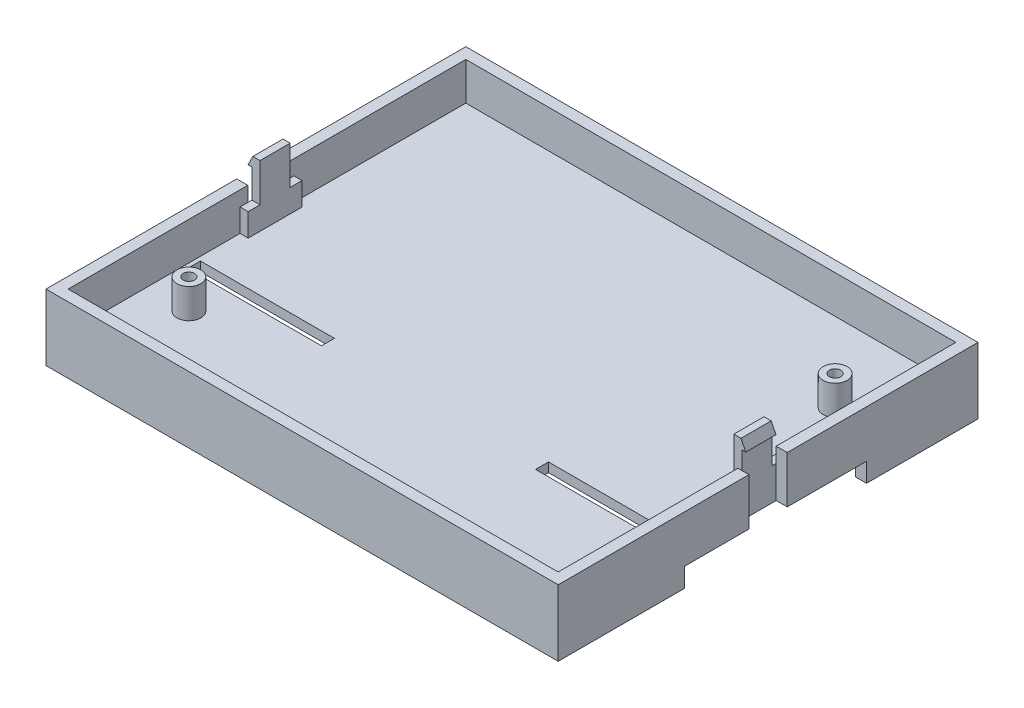
SolidWorks part; units mm, degrees
ref_plane "Alzado" through (0, 0, 0) normal (0, 0, 1) x (1, 0, 0)
ref_plane "Planta" through (0, 0, 0) normal (0, 1, 0) x (1, 0, 0)
ref_plane "Vista lateral" through (0, 0, 0) normal (1, 0, 0) x (0, 0, -1)
sketch "Sketch1" plane through (0, 0, 0) normal (0, 1, 0) x (1, 0, 0)
  line L1 (-53.5, -43.85) -> (53.5, -43.85)
  line L2 (-53.5, -43.85) -> (-53.5, 43.85)
  line L3 (-53.5, 43.85) -> (53.5, 43.85)
  line L4 (53.5, -43.85) -> (53.5, 43.85)
  line L5 (-53.5, -43.85) -> (53.5, 43.85) construction
  line L6 (-53.5, 43.85) -> (53.5, -43.85) construction
  point P0 (0, 0)
  dimension "D1" = 107
  dimension "D2" = 87.7
extrude "Boss-Extrude1" add sketch "Sketch1" along normal blind 13.85
sketch "Sketch2" plane through (0, 13.85, 0) normal (0, 1, 0) x (1, 0, 0)
  line L8 (51.19, -41.54) -> (51.19, 41.54)
  line L9 (51.19, 41.54) -> (-51.19, 41.54)
  line L10 (-51.19, 41.54) -> (-51.19, -41.54)
  line L11 (-51.19, -41.54) -> (51.19, -41.54)
  line L12 (51.19, -41.54) -> (51.19, 41.54)
  line L13 (51.19, 41.54) -> (-51.19, 41.54)
  line L14 (-51.19, 41.54) -> (-51.19, -41.54)
  line L15 (-51.19, -41.54) -> (51.19, -41.54)
  dimension "D1" = 2.31
extrude "Cut-Extrude1" cut sketch "Sketch2" against normal blind 7.9
sketch "Sketch3" plane through (0, 0, 0) normal (0, -1, 0) x (1, 0, 0)
  line L0 (-51.19, -41.54) -> (-51.19, 41.54) construction
  line L1 (-51.19, 41.54) -> (51.19, 41.54)
  line L2 (-51.19, 41.54) -> (-51.19, 19.24)
  line L3 (-51.19, 19.24) -> (-23.5, 19.24)
  line L4 (51.19, 41.54) -> (51.19, 19.24)
  line L5 (-51.19, 41.54) -> (51.19, 41.54) construction
  line L6 (51.19, 41.54) -> (51.19, -41.54) construction
  line L7 (-23.5, 19.24) -> (-23.5, 14.74)
  line L8 (-23.5, 14.74) -> (-49.4, 14.74)
  line L9 (-53.5, -43.85) -> (-53.5, 43.85) construction
  line L10 (-53.5, 17.44) -> (-53.5, -20.56)
  line L11 (-41.0677, -20.56) -> (-6.19, -20.56)
  line L12 (53.5, 43.85) -> (53.5, -43.85) construction
  line L13 (53.5, -20.56) -> (53.5, 17.44)
  line L14 (0, 0) -> (0, 18.4212) construction
  line L15 (23.5, 14.74) -> (23.5, 19.24)
  line L16 (23.5, 19.24) -> (51.19, 19.24)
  line L17 (-51.19, -41.54) -> (-10.19, -41.54)
  line L18 (51.19, -41.54) -> (51.19, -20.56)
  line L19 (-51.19, -41.54) -> (-51.19, -20.56)
  line L20 (-10.19, -41.54) -> (-10.19, -22.86)
  line L21 (10.19, -41.54) -> (10.19, -22.86)
  line L22 (6.19, -20.56) -> (6.19, -43.85)
  line L23 (-6.19, -43.85) -> (6.19, -43.85)
  line L24 (51.19, -20.56) -> (53.5, -20.56)
  line L25 (10.19, -41.54) -> (51.19, -41.54)
  line L26 (53.5, -43.85) -> (-53.5, -43.85) construction
  line L28 (51.19, -41.54) -> (-51.19, -41.54) construction
  line L29 (-10.19, -22.86) -> (-40.69, -22.86)
  line L30 (42.7044, -23.54) -> (40.69, -22.86)
  line L31 (-51.19, -20.56) -> (-53.5, -20.56)
  line L32 (-41.0677, -20.56) -> (-43.44, -21.3608)
  line L33 (-43.44, -21.3608) -> (-42.7044, -23.54)
  line L34 (-42.7044, -23.54) -> (-40.69, -22.86)
  line L35 (43.44, -21.3608) -> (42.7044, -23.54)
  line L36 (41.0677, -20.56) -> (43.44, -21.3608)
  line L37 (10.19, -22.86) -> (40.69, -22.86)
  line L38 (41.0677, -20.56) -> (6.19, -20.56)
  line L39 (-49.4, 17.44) -> (-53.5, 17.44)
  line L40 (-49.4, 17.44) -> (-49.4, 14.74)
  line L41 (49.4, 17.44) -> (53.5, 17.44)
  line L42 (49.4, 17.44) -> (49.4, 14.74)
  line L43 (23.5, 14.74) -> (49.4, 14.74)
  line L44 (-6.19, -20.56) -> (-6.19, -43.85)
  dimension "D1" = 22.3
  dimension "D2" = 30
  dimension "D3" = 4.5
  dimension "D4" = 4
  dimension "D5" = 4
  dimension "D6" = 41
  dimension "D7" = 2.3
  dimension "D8" = 7.75
  dimension "D9" = 2.3
  dimension "D10" = 35.3
  dimension "D11" = 18
  dimension "D12" = 30.5
  dimension "D13" = 30.5
  dimension "D14" = 25.9
  dimension "D15" = 1.8
extrude "Cut-Extrude2" cut sketch "Sketch3" against normal blind 4
sketch "Sketch4" plane through (0, 5.95, 0) normal (0, 1, 0) x (1, 0, 0)
  circle A0 centre (42.5, 25) radius 1.2
  circle A1 centre (-42.5, -25) radius 1.2
  circle A2 centre (-42.5, -25) radius 2.5
  circle A3 centre (42.5, 25) radius 2.5
  dimension "D1" = 2.4
  dimension "D6" = 5
  dimension "D2" = 25
  dimension "D3" = 25
  dimension "D4" = 42.5
  dimension "D5" = 42.5
extrude "Boss-Extrude2" add sketch "Sketch4" along normal blind 6.2
sketch "Sketch5" plane through (0, 5.95, 0) normal (0, 1, 0) x (1, 0, 0)
  line L0 (-49.4, -17.44) -> (-53.5, -17.44) construction
  line L1 (-50.36, -17.44) -> (-22.36, -17.44)
  line L2 (-50.36, -17.44) -> (-50.36, -14.74)
  line L3 (-50.36, -14.74) -> (-22.36, -14.74)
  line L4 (-22.36, -17.44) -> (-22.36, -14.74)
  line L5 (-23.5, -14.74) -> (-49.4, -14.74) construction
  line L6 (-53.5, 43.85) -> (-53.5, -43.85) construction
  line L7 (0, 0) -> (0, -23.0009) construction
  line L8 (22.36, -17.44) -> (22.36, -14.74)
  line L9 (50.36, -14.74) -> (22.36, -14.74)
  line L10 (50.36, -17.44) -> (50.36, -14.74)
  line L11 (50.36, -17.44) -> (22.36, -17.44)
  dimension "D1" = 3.14
  dimension "D2" = 28
extrude "Cut-Extrude3" cut sketch "Sketch5" against normal blind 3.5
chamfer "Chamfer1" distance 2 angle 45 2 edges at (-36.45, 2.45, 14.74) (36.45, 2.45, 14.74)
sketch "Sketch6" plane through (-53.5, 0, 0) normal (-1, 0, 0) x (0, 0, 1)
  line L0 (-43.85, 13.85) -> (43.85, 13.85) construction
  line L1 (-4, 13.85) -> (4, 13.85)
  line L2 (-4, 13.85) -> (-4, 4)
  line L3 (-4, 4) -> (4, 4)
  line L4 (4, 13.85) -> (4, 4)
  line L5 (17.44, 4) -> (-20.56, 4) construction
  point P8 (0, 4)
  dimension "D1" = 8
extrude "Cut-Extrude4" cut sketch "Sketch6" against normal blind 2.31
sketch "Sketch7" plane through (-51.19, 0, 0) normal (1, 0, 0) x (0, 0, -1)
  line L0 (-4, 5.95) -> (-41.54, 5.95) construction
  line L1 (-5.625, 5.95) -> (5.625, 5.95)
  line L2 (-5.625, 5.95) -> (-5.625, 10.75)
  line L3 (-5.625, 10.75) -> (5.625, 10.75)
  line L4 (5.625, 5.95) -> (5.625, 10.75)
  point P6 (0, 5.95)
  dimension "D1" = 11.25
  dimension "D2" = 4.8
extrude "Boss-Extrude3" add sketch "Sketch7" along normal blind 1.7
sketch "Sketch8" plane through (0, 0, 0) normal (0, 0, 1) x (1, 0, 0)
  line L0 (-49.49, 10.75) -> (-49.49, 18.75)
  line L1 (-49.49, 18.75) -> (-50.99, 18.75)
  line L2 (-50.99, 18.75) -> (-51.99, 16.75)
  line L3 (-51.99, 16.75) -> (-51.19, 16.75)
  line L4 (-51.19, 16.75) -> (-51.19, 10.75)
  line L5 (-51.19, 10.75) -> (-49.49, 10.75)
  line L6 (51.19, 5.95) -> (-51.19, 5.95) construction
  dimension "D1" = 12.8
  dimension "D2" = 2.5
  dimension "D3" = 2
  dimension "D4" = 1.5
extrude "Boss-Extrude4" add sketch "Sketch8" along normal mid plane 6.3
mirror "Mirror1" about plane through (0, 0, 0) normal (1, 0, 0) of "Cut-Extrude4", "Boss-Extrude3", "Boss-Extrude4"
